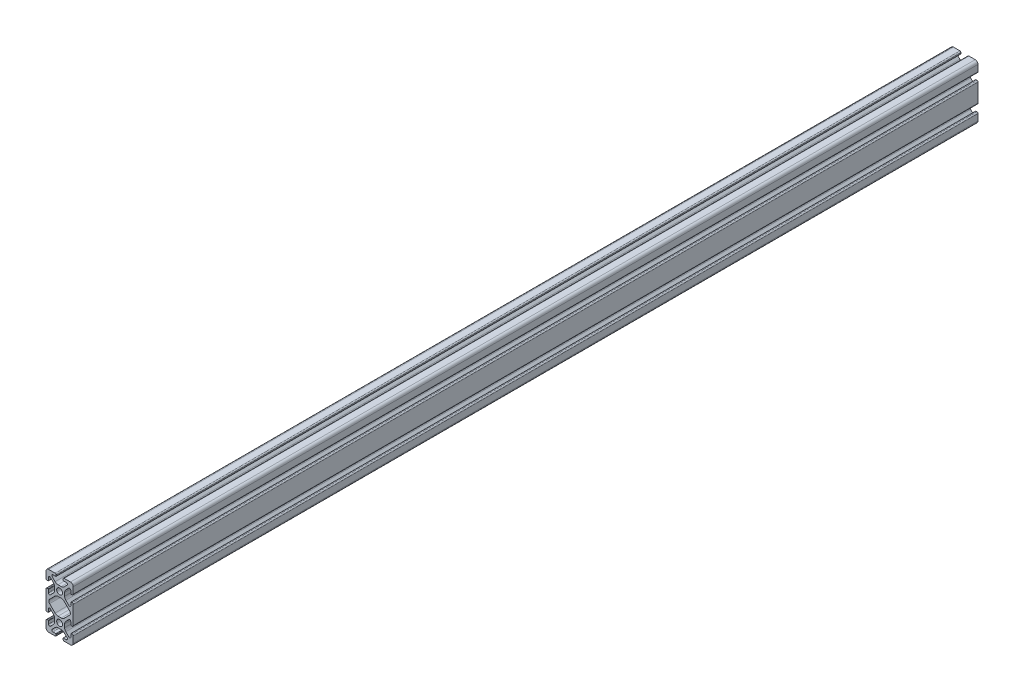
SolidWorks part; units mm, degrees
ref_plane "Front Plane" through (0, 0, 0) normal (0, 0, 1) x (1, 0, 0)
ref_plane "Top Plane" through (0, 0, 0) normal (0, 1, 0) x (1, 0, 0)
ref_plane "Right Plane" through (0, 0, 0) normal (1, 0, 0) x (0, 0, -1)
sketch "Sketch1" plane through (0, 0, 0) normal (0, 0, 1) x (1, 0, 0)
  line L0 (0, 10) -> (0, 20) construction
  line L1 (0, 10) -> (10, 10) construction
  line L2 (0, 10) -> (-10, 20) construction
  line L3 (-8, 20) -> (-3.3, 20)
  line L4 (-10, 20) -> (0, 20) construction
  line L6 (-2.8, 18.2) -> (-4.9051, 18.2)
  line L10 (0, 13.7) -> (-1.2022, 13.7)
  line L11 (-3.3236, 14.5787) -> (-5.5025, 16.7576)
  line L24 (0, 10) -> (-10, 10) construction
  line L25 (-10, 10) -> (0, 10) construction
  line L27 (-10, 0) -> (-10, 20) construction
  line L28 (0, 20) -> (10, 20) construction
  line L29 (-2.5, 18.5) -> (-2.5, 19.2)
  line L30 (-10, -20) -> (10, -20) construction
  line L31 (0, 20) -> (0, -20) construction
  arc A0 (-9.4142, 19.4142) -> (-8, 20) centre (-8, 18) cw
  arc A5 (-3.3, 20) -> (-2.5, 19.2) centre (-3.3, 19.2) cw
  arc A6 (-1.2022, 13.7) -> (-3.3236, 14.5787) centre (-1.2022, 16.7) cw
  circle A16 centre (0, 10) radius 2.15
  arc A18 (-5.5025, 16.7576) -> (-4.9051, 18.2) centre (-4.9051, 17.3551) cw
  arc A20 (-2.8, 18.2) -> (-2.5, 18.5) centre (-2.8, 18.5) ccw
  point P15 (0, -20)
  point P24 (0, 0)
  point P42 (-2.4449, 13.7)
  point P80 (-10, 10)
  dimension "D11" = 2
  dimension "D15" = 3
  dimension "Center Hole Diameter" = 4.3
  dimension "D7" = 0.8
  dimension "D8" = 0.3
  dimension "D4" = 0.8449
  dimension "D1" = 45
  dimension "Rail Width" = 20
  dimension "T-Slot Depth" = 6.3
  dimension "D9" = 1.8
  dimension "D23" = 7.4
  dimension "D5" = 11.5
  dimension "T-Slot Width" = 5
  dimension "D3" = 1.775
  dimension "D6" = 9.8102
  dimension "Rail Height" = 40
sketch "Sketch2" plane through (0, 0, 0) normal (1, 0, 0) x (0, 0, -1)
  line L0 (-304.8, 0) -> (304.8, 0)
  line L1 (-304.8, -20) -> (-304.8, 20)
  line L2 (0, 10) -> (0, 20) construction
  line L3 (0, 0) -> (0, 20) construction
  line L4 (304.8, -20) -> (304.8, 20)
  line L5 (-10, 10) -> (10, 10) construction
  point P0 (-279.8, 0)
  point P3 (0, 0)
  point P7 (279.8, 0)
  point P11 (-304.8, 0)
  point P14 (304.8, 0)
  point P23 (0, 10)
  dimension "D1" = 25
  dimension "Length" = 609.6
sketch "Sketch3" plane through (0, 0, 0) normal (0, 0, 1) x (1, 0, 0)
  line L0 (-2.5, 18.5) -> (-2.5, 19.2) construction
  line L1 (0, 10) -> (-10, 20) construction
  line L2 (0, 10) -> (-10, 20) construction
  line L5 (-8, 20) -> (-3.3, 20) construction
  line L6 (-2.8, 18.2) -> (-4.9051, 18.2) construction
  line L7 (-8.5, 7.5) -> (-9.2, 7.5)
  line L17 (-2.5, 18.5) -> (-2.5, 19.2)
  line L19 (-2.8, 18.2) -> (-4.9051, 18.2)
  line L21 (-3.7, 10) -> (0, 10) construction
  line L22 (-3.7, 8.7978) -> (-3.7, 11.2022)
  line L23 (-4.5787, 13.3236) -> (-6.7576, 15.5025)
  line L42 (-3.3236, 14.5787) -> (-5.5025, 16.7576) construction
  line L43 (0, 13.7) -> (-1.2022, 13.7) construction
  line L44 (-8, 20) -> (-3.3, 20)
  line L47 (-3.3236, 14.5787) -> (-5.5025, 16.7576)
  line L48 (1.2022, 13.7) -> (-1.2022, 13.7)
  line L59 (0, 13.7) -> (0, 12.15) construction
  line L60 (-10, 18) -> (-10, 13.3)
  line L61 (-8.2, 12.8) -> (-8.2, 14.9051)
  line L62 (-8.5, 12.5) -> (-9.2, 12.5)
  line L63 (-8.2, 7.2) -> (-8.2, 5.0949)
  line L64 (-10, 0) -> (-10, 6.7)
  line L65 (1.2022, 6.3) -> (-1.2022, 6.3)
  line L66 (-3.3236, 5.4213) -> (-7.3307, 1.4142)
  line L68 (-4.5787, 6.6764) -> (-6.7576, 4.4975)
  line L73 (10, 0) -> (-10, 0) construction
  line L78 (4.5787, 6.6764) -> (6.7576, 4.4975)
  line L79 (3.3236, 5.4213) -> (7.3307, 1.4142)
  line L81 (10, 0) -> (10, 6.7)
  line L82 (8.2, 7.2) -> (8.2, 5.0949)
  line L83 (8.5, 12.5) -> (9.2, 12.5)
  line L84 (8.2, 12.8) -> (8.2, 14.9051)
  line L85 (10, 18) -> (10, 13.3)
  line L87 (3.3236, 14.5787) -> (5.5025, 16.7576)
  line L88 (8, 20) -> (3.3, 20)
  line L89 (4.5787, 13.3236) -> (6.7576, 15.5025)
  line L90 (3.7, 8.7978) -> (3.7, 11.2022)
  line L91 (2.8, 18.2) -> (4.9051, 18.2)
  line L92 (2.5, 18.5) -> (2.5, 19.2)
  line L93 (8.5, 7.5) -> (9.2, 7.5)
  line L94 (-10, 0) -> (-7.9165, 0)
  line L96 (7.9165, 0) -> (10, 0)
  arc A0 (-8, 20) -> (-9.4142, 19.4142) centre (-8, 18) ccw construction
  arc A1 (-2.8, 18.2) -> (-2.5, 18.5) centre (-2.8, 18.5) ccw construction
  arc A3 (-2.8, 18.2) -> (-2.5, 18.5) centre (-2.8, 18.5) ccw
  arc A5 (-8, 20) -> (-10, 18) centre (-8, 18) ccw
  arc A10 (-3.3236, 5.4213) -> (-1.2022, 6.3) centre (-1.2022, 3.3) cw
  circle A13 centre (0, 10) radius 2.15 construction
  circle A14 centre (0, 10) radius 2.15
  arc A15 (-4.5787, 13.3236) -> (-3.7, 11.2022) centre (-6.7, 11.2022) cw
  arc A16 (-8.2, 14.9051) -> (-6.7576, 15.5025) centre (-7.3551, 14.9051) cw
  arc A17 (-9.2, 12.5) -> (-10, 13.3) centre (-9.2, 13.3) cw
  arc A18 (-8.2, 12.8) -> (-8.5, 12.5) centre (-8.5, 12.8) cw
  arc A36 (-2.5, 19.2) -> (-3.3, 20) centre (-3.3, 19.2) ccw construction
  arc A38 (-4.9051, 18.2) -> (-5.5025, 16.7576) centre (-4.9051, 17.3551) ccw construction
  arc A39 (-3.3236, 14.5787) -> (-1.2022, 13.7) centre (-1.2022, 16.7) ccw construction
  arc A41 (-2.5, 19.2) -> (-3.3, 20) centre (-3.3, 19.2) ccw
  arc A43 (-4.9051, 18.2) -> (-5.5025, 16.7576) centre (-4.9051, 17.3551) ccw
  arc A44 (-3.3236, 14.5787) -> (-1.2022, 13.7) centre (-1.2022, 16.7) ccw
  arc A47 (-8.2, 7.2) -> (-8.5, 7.5) centre (-8.5, 7.2) ccw
  arc A48 (-9.2, 7.5) -> (-10, 6.7) centre (-9.2, 6.7) ccw
  arc A49 (-8.2, 5.0949) -> (-6.7576, 4.4975) centre (-7.3551, 5.0949) ccw
  arc A50 (-4.5787, 6.6764) -> (-3.7, 8.7978) centre (-6.7, 8.7978) ccw
  arc A54 (-7.9165, 0) -> (-7.3307, 1.4142) centre (-5.9165, 0) cw
  arc A57 (7.9165, 0) -> (7.3307, 1.4142) centre (5.9165, 0) ccw
  arc A58 (4.5787, 6.6764) -> (3.7, 8.7978) centre (6.7, 8.7978) cw
  arc A59 (8.2, 5.0949) -> (6.7576, 4.4975) centre (7.3551, 5.0949) cw
  arc A60 (9.2, 7.5) -> (10, 6.7) centre (9.2, 6.7) cw
  arc A61 (8.2, 7.2) -> (8.5, 7.5) centre (8.5, 7.2) cw
  arc A62 (3.3236, 14.5787) -> (1.2022, 13.7) centre (1.2022, 16.7) cw
  arc A63 (4.9051, 18.2) -> (5.5025, 16.7576) centre (4.9051, 17.3551) cw
  arc A64 (2.5, 19.2) -> (3.3, 20) centre (3.3, 19.2) cw
  arc A65 (8.2, 12.8) -> (8.5, 12.5) centre (8.5, 12.8) ccw
  arc A66 (9.2, 12.5) -> (10, 13.3) centre (9.2, 13.3) ccw
  arc A67 (8.2, 14.9051) -> (6.7576, 15.5025) centre (7.3551, 14.9051) ccw
  arc A68 (4.5787, 13.3236) -> (3.7, 11.2022) centre (6.7, 11.2022) ccw
  arc A70 (3.3236, 5.4213) -> (1.2022, 6.3) centre (1.2022, 3.3) ccw
  arc A71 (8, 20) -> (10, 18) centre (8, 18) cw
  arc A72 (2.8, 18.2) -> (2.5, 18.5) centre (2.8, 18.5) cw
  point P59 (-10, 2)
  point P71 (0, 0)
  point P116 (0, 6.3)
extrude "Boss-Extrude1" add sketch "Sketch3" along normal mid plane 609.6
pattern_circular "CirPattern1" count 2 over 360 about axis through (0, 0, 0) along (0, 0, 1) of "Boss-Extrude1"
sketch "Sketch4" plane through (0, 0, 304.8) normal (0, 0, 1) x (1, 0, 0)
  line L0 (7.3307, -1.4142) -> (3.3236, -5.4213) construction
  line L1 (-3.3236, -5.4213) -> (-7.3307, -1.4142) construction
  line L2 (1.2022, -6.3) -> (-1.2022, -6.3) construction
  line L3 (3.3236, 5.4213) -> (7.3307, 1.4142) construction
  line L4 (-1.2022, 6.3) -> (1.2022, 6.3) construction
  line L5 (-7.3307, 1.4142) -> (-3.3236, 5.4213) construction
  line L6 (7.3307, -1.4142) -> (3.3236, -5.4213)
  line L7 (-3.3236, -5.4213) -> (-7.3307, -1.4142)
  line L8 (1.2022, -6.3) -> (-1.2022, -6.3)
  line L9 (3.3236, 5.4213) -> (7.3307, 1.4142)
  line L10 (-1.2022, 6.3) -> (1.2022, 6.3)
  line L11 (-7.3307, 1.4142) -> (-3.3236, 5.4213)
  line L52 (-2.5, 18.5) -> (-2.5, 19.2)
  line L53 (-3.3, 20) -> (-8, 20)
  line L54 (-10, 18) -> (-10, 13.3)
  line L55 (-9.2, 12.5) -> (-8.5, 12.5)
  line L56 (-8.2, 12.8) -> (-8.2, 14.9051)
  line L57 (-6.7576, 15.5025) -> (-4.5787, 13.3236)
  line L58 (-3.7, 11.2022) -> (-3.7, 8.7978)
  line L59 (-4.5787, 6.6764) -> (-6.7576, 4.4975)
  line L60 (-8.2, 5.0949) -> (-8.2, 7.2)
  line L61 (-8.5, 7.5) -> (-9.2, 7.5)
  line L62 (-10, 6.7) -> (-10, -6.7)
  line L63 (-9.2, -7.5) -> (-8.5, -7.5)
  line L64 (-8.2, -7.2) -> (-8.2, -5.0949)
  line L65 (-6.7576, -4.4975) -> (-4.5787, -6.6764)
  line L66 (-3.7, -8.7978) -> (-3.7, -11.2022)
  line L67 (-4.5787, -13.3236) -> (-6.7576, -15.5025)
  line L68 (-8.2, -14.9051) -> (-8.2, -12.8)
  line L69 (-8.5, -12.5) -> (-9.2, -12.5)
  line L70 (-10, -13.3) -> (-10, -18)
  line L71 (-8, -20) -> (-3.3, -20)
  line L72 (-2.5, -19.2) -> (-2.5, -18.5)
  line L73 (-2.8, -18.2) -> (-4.9051, -18.2)
  line L74 (-5.5025, -16.7576) -> (-3.3236, -14.5787)
  line L75 (-1.2022, -13.7) -> (1.2022, -13.7)
  line L76 (3.3236, -14.5787) -> (5.5025, -16.7576)
  line L77 (4.9051, -18.2) -> (2.8, -18.2)
  line L78 (2.5, -18.5) -> (2.5, -19.2)
  line L79 (3.3, -20) -> (8, -20)
  line L80 (10, -18) -> (10, -13.3)
  line L81 (9.2, -12.5) -> (8.5, -12.5)
  line L82 (8.2, -12.8) -> (8.2, -14.9051)
  line L83 (6.7576, -15.5025) -> (4.5787, -13.3236)
  line L84 (3.7, -11.2022) -> (3.7, -8.7978)
  line L85 (4.5787, -6.6764) -> (6.7576, -4.4975)
  line L86 (8.2, -5.0949) -> (8.2, -7.2)
  line L87 (8.5, -7.5) -> (9.2, -7.5)
  line L88 (10, -6.7) -> (10, 6.7)
  line L89 (9.2, 7.5) -> (8.5, 7.5)
  line L90 (8.2, 7.2) -> (8.2, 5.0949)
  line L91 (6.7576, 4.4975) -> (4.5787, 6.6764)
  line L92 (3.7, 8.7978) -> (3.7, 11.2022)
  line L93 (4.5787, 13.3236) -> (6.7576, 15.5025)
  line L94 (8.2, 14.9051) -> (8.2, 12.8)
  line L95 (8.5, 12.5) -> (9.2, 12.5)
  line L96 (10, 13.3) -> (10, 18)
  line L97 (8, 20) -> (3.3, 20)
  line L98 (2.5, 19.2) -> (2.5, 18.5)
  line L99 (2.8, 18.2) -> (4.9051, 18.2)
  line L100 (5.5025, 16.7576) -> (3.3236, 14.5787)
  line L101 (1.2022, 13.7) -> (-1.2022, 13.7)
  line L102 (-3.3236, 14.5787) -> (-5.5025, 16.7576)
  line L103 (-4.9051, 18.2) -> (-2.8, 18.2)
  line L104 (-2.5, 18.5) -> (-2.5, 19.2)
  line L105 (-3.3, 20) -> (-8, 20)
  line L106 (-10, 18) -> (-10, 13.3)
  line L107 (-9.2, 12.5) -> (-8.5, 12.5)
  line L108 (-8.2, 12.8) -> (-8.2, 14.9051)
  line L109 (-6.7576, 15.5025) -> (-4.5787, 13.3236)
  line L110 (-3.7, 11.2022) -> (-3.7, 8.7978)
  line L111 (-4.5787, 6.6764) -> (-6.7576, 4.4975)
  line L112 (-8.2, 5.0949) -> (-8.2, 7.2)
  line L113 (-8.5, 7.5) -> (-9.2, 7.5)
  line L114 (-10, 6.7) -> (-10, -6.7)
  line L115 (-9.2, -7.5) -> (-8.5, -7.5)
  line L116 (-8.2, -7.2) -> (-8.2, -5.0949)
  line L117 (-6.7576, -4.4975) -> (-4.5787, -6.6764)
  line L118 (-3.7, -8.7978) -> (-3.7, -11.2022)
  line L119 (-4.5787, -13.3236) -> (-6.7576, -15.5025)
  line L120 (-8.2, -14.9051) -> (-8.2, -12.8)
  line L121 (-8.5, -12.5) -> (-9.2, -12.5)
  line L122 (-10, -13.3) -> (-10, -18)
  line L123 (-8, -20) -> (-3.3, -20)
  line L124 (-2.5, -19.2) -> (-2.5, -18.5)
  line L125 (-2.8, -18.2) -> (-4.9051, -18.2)
  line L126 (-5.5025, -16.7576) -> (-3.3236, -14.5787)
  line L127 (-1.2022, -13.7) -> (1.2022, -13.7)
  line L128 (3.3236, -14.5787) -> (5.5025, -16.7576)
  line L129 (4.9051, -18.2) -> (2.8, -18.2)
  line L130 (2.5, -18.5) -> (2.5, -19.2)
  line L131 (3.3, -20) -> (8, -20)
  line L132 (10, -18) -> (10, -13.3)
  line L133 (9.2, -12.5) -> (8.5, -12.5)
  line L134 (8.2, -12.8) -> (8.2, -14.9051)
  line L135 (6.7576, -15.5025) -> (4.5787, -13.3236)
  line L136 (3.7, -11.2022) -> (3.7, -8.7978)
  line L137 (4.5787, -6.6764) -> (6.7576, -4.4975)
  line L138 (8.2, -5.0949) -> (8.2, -7.2)
  line L139 (8.5, -7.5) -> (9.2, -7.5)
  line L140 (10, -6.7) -> (10, 6.7)
  line L141 (9.2, 7.5) -> (8.5, 7.5)
  line L142 (8.2, 7.2) -> (8.2, 5.0949)
  line L143 (6.7576, 4.4975) -> (4.5787, 6.6764)
  line L144 (3.7, 8.7978) -> (3.7, 11.2022)
  line L145 (4.5787, 13.3236) -> (6.7576, 15.5025)
  line L146 (8.2, 14.9051) -> (8.2, 12.8)
  line L147 (8.5, 12.5) -> (9.2, 12.5)
  line L148 (10, 13.3) -> (10, 18)
  line L149 (8, 20) -> (3.3, 20)
  line L150 (2.5, 19.2) -> (2.5, 18.5)
  line L151 (2.8, 18.2) -> (4.9051, 18.2)
  line L152 (5.5025, 16.7576) -> (3.3236, 14.5787)
  line L153 (1.2022, 13.7) -> (-1.2022, 13.7)
  line L154 (-3.3236, 14.5787) -> (-5.5025, 16.7576)
  line L155 (-4.9051, 18.2) -> (-2.8, 18.2)
  circle A0 centre (0, 10) radius 2.15 construction
  arc A1 (-7.3307, 1.4142) -> (-7.3307, -1.4142) centre (-5.9165, 0) ccw construction
  arc A2 (-3.3236, -5.4213) -> (-1.2022, -6.3) centre (-1.2022, -3.3) ccw construction
  arc A3 (1.2022, -6.3) -> (3.3236, -5.4213) centre (1.2022, -3.3) ccw construction
  circle A4 centre (0, -10) radius 2.15 construction
  arc A5 (7.3307, -1.4142) -> (7.3307, 1.4142) centre (5.9165, 0) ccw construction
  arc A6 (3.3236, 5.4213) -> (1.2022, 6.3) centre (1.2022, 3.3) ccw construction
  arc A7 (-1.2022, 6.3) -> (-3.3236, 5.4213) centre (-1.2022, 3.3) ccw construction
  circle A8 centre (0, 10) radius 2.15
  arc A9 (-7.3307, 1.4142) -> (-7.3307, -1.4142) centre (-5.9165, 0) ccw
  arc A10 (-3.3236, -5.4213) -> (-1.2022, -6.3) centre (-1.2022, -3.3) ccw
  arc A11 (1.2022, -6.3) -> (3.3236, -5.4213) centre (1.2022, -3.3) ccw
  circle A12 centre (0, -10) radius 2.15
  arc A13 (7.3307, -1.4142) -> (7.3307, 1.4142) centre (5.9165, 0) ccw
  arc A14 (3.3236, 5.4213) -> (1.2022, 6.3) centre (1.2022, 3.3) ccw
  arc A15 (-1.2022, 6.3) -> (-3.3236, 5.4213) centre (-1.2022, 3.3) ccw
  arc A52 (-2.8, 18.2) -> (-2.5, 18.5) centre (-2.8, 18.5) ccw
  arc A53 (-2.5, 19.2) -> (-3.3, 20) centre (-3.3, 19.2) ccw
  arc A54 (-8, 20) -> (-10, 18) centre (-8, 18) ccw
  arc A55 (-10, 13.3) -> (-9.2, 12.5) centre (-9.2, 13.3) ccw
  arc A56 (-8.5, 12.5) -> (-8.2, 12.8) centre (-8.5, 12.8) ccw
  arc A57 (-6.7576, 15.5025) -> (-8.2, 14.9051) centre (-7.3551, 14.9051) ccw
  arc A58 (-3.7, 11.2022) -> (-4.5787, 13.3236) centre (-6.7, 11.2022) ccw
  arc A59 (-4.5787, 6.6764) -> (-3.7, 8.7978) centre (-6.7, 8.7978) ccw
  arc A60 (-8.2, 5.0949) -> (-6.7576, 4.4975) centre (-7.3551, 5.0949) ccw
  arc A61 (-8.2, 7.2) -> (-8.5, 7.5) centre (-8.5, 7.2) ccw
  arc A62 (-9.2, 7.5) -> (-10, 6.7) centre (-9.2, 6.7) ccw
  arc A63 (-10, -6.7) -> (-9.2, -7.5) centre (-9.2, -6.7) ccw
  arc A64 (-8.5, -7.5) -> (-8.2, -7.2) centre (-8.5, -7.2) ccw
  arc A65 (-6.7576, -4.4975) -> (-8.2, -5.0949) centre (-7.3551, -5.0949) ccw
  arc A66 (-3.7, -8.7978) -> (-4.5787, -6.6764) centre (-6.7, -8.7978) ccw
  arc A67 (-4.5787, -13.3236) -> (-3.7, -11.2022) centre (-6.7, -11.2022) ccw
  arc A68 (-8.2, -14.9051) -> (-6.7576, -15.5025) centre (-7.3551, -14.9051) ccw
  arc A69 (-8.2, -12.8) -> (-8.5, -12.5) centre (-8.5, -12.8) ccw
  arc A70 (-9.2, -12.5) -> (-10, -13.3) centre (-9.2, -13.3) ccw
  arc A71 (-10, -18) -> (-8, -20) centre (-8, -18) ccw
  arc A72 (-3.3, -20) -> (-2.5, -19.2) centre (-3.3, -19.2) ccw
  arc A73 (-2.5, -18.5) -> (-2.8, -18.2) centre (-2.8, -18.5) ccw
  arc A74 (-5.5025, -16.7576) -> (-4.9051, -18.2) centre (-4.9051, -17.3551) ccw
  arc A75 (-1.2022, -13.7) -> (-3.3236, -14.5787) centre (-1.2022, -16.7) ccw
  arc A76 (3.3236, -14.5787) -> (1.2022, -13.7) centre (1.2022, -16.7) ccw
  arc A77 (4.9051, -18.2) -> (5.5025, -16.7576) centre (4.9051, -17.3551) ccw
  arc A78 (2.8, -18.2) -> (2.5, -18.5) centre (2.8, -18.5) ccw
  arc A79 (2.5, -19.2) -> (3.3, -20) centre (3.3, -19.2) ccw
  arc A80 (8, -20) -> (10, -18) centre (8, -18) ccw
  arc A81 (10, -13.3) -> (9.2, -12.5) centre (9.2, -13.3) ccw
  arc A82 (8.5, -12.5) -> (8.2, -12.8) centre (8.5, -12.8) ccw
  arc A83 (6.7576, -15.5025) -> (8.2, -14.9051) centre (7.3551, -14.9051) ccw
  arc A84 (3.7, -11.2022) -> (4.5787, -13.3236) centre (6.7, -11.2022) ccw
  arc A85 (4.5787, -6.6764) -> (3.7, -8.7978) centre (6.7, -8.7978) ccw
  arc A86 (8.2, -5.0949) -> (6.7576, -4.4975) centre (7.3551, -5.0949) ccw
  arc A87 (8.2, -7.2) -> (8.5, -7.5) centre (8.5, -7.2) ccw
  arc A88 (9.2, -7.5) -> (10, -6.7) centre (9.2, -6.7) ccw
  arc A89 (10, 6.7) -> (9.2, 7.5) centre (9.2, 6.7) ccw
  arc A90 (8.5, 7.5) -> (8.2, 7.2) centre (8.5, 7.2) ccw
  arc A91 (6.7576, 4.4975) -> (8.2, 5.0949) centre (7.3551, 5.0949) ccw
  arc A92 (3.7, 8.7978) -> (4.5787, 6.6764) centre (6.7, 8.7978) ccw
  arc A93 (4.5787, 13.3236) -> (3.7, 11.2022) centre (6.7, 11.2022) ccw
  arc A94 (8.2, 14.9051) -> (6.7576, 15.5025) centre (7.3551, 14.9051) ccw
  arc A95 (8.2, 12.8) -> (8.5, 12.5) centre (8.5, 12.8) ccw
  arc A96 (9.2, 12.5) -> (10, 13.3) centre (9.2, 13.3) ccw
  arc A97 (10, 18) -> (8, 20) centre (8, 18) ccw
  arc A98 (3.3, 20) -> (2.5, 19.2) centre (3.3, 19.2) ccw
  arc A99 (2.5, 18.5) -> (2.8, 18.2) centre (2.8, 18.5) ccw
  arc A100 (5.5025, 16.7576) -> (4.9051, 18.2) centre (4.9051, 17.3551) ccw
  arc A101 (1.2022, 13.7) -> (3.3236, 14.5787) centre (1.2022, 16.7) ccw
  arc A102 (-3.3236, 14.5787) -> (-1.2022, 13.7) centre (-1.2022, 16.7) ccw
  arc A103 (-4.9051, 18.2) -> (-5.5025, 16.7576) centre (-4.9051, 17.3551) ccw
  arc A104 (-2.8, 18.2) -> (-2.5, 18.5) centre (-2.8, 18.5) ccw
  arc A105 (-2.5, 19.2) -> (-3.3, 20) centre (-3.3, 19.2) ccw
  arc A106 (-8, 20) -> (-10, 18) centre (-8, 18) ccw
  arc A107 (-10, 13.3) -> (-9.2, 12.5) centre (-9.2, 13.3) ccw
  arc A108 (-8.5, 12.5) -> (-8.2, 12.8) centre (-8.5, 12.8) ccw
  arc A109 (-6.7576, 15.5025) -> (-8.2, 14.9051) centre (-7.3551, 14.9051) ccw
  arc A110 (-3.7, 11.2022) -> (-4.5787, 13.3236) centre (-6.7, 11.2022) ccw
  arc A111 (-4.5787, 6.6764) -> (-3.7, 8.7978) centre (-6.7, 8.7978) ccw
  arc A112 (-8.2, 5.0949) -> (-6.7576, 4.4975) centre (-7.3551, 5.0949) ccw
  arc A113 (-8.2, 7.2) -> (-8.5, 7.5) centre (-8.5, 7.2) ccw
  arc A114 (-9.2, 7.5) -> (-10, 6.7) centre (-9.2, 6.7) ccw
  arc A115 (-10, -6.7) -> (-9.2, -7.5) centre (-9.2, -6.7) ccw
  arc A116 (-8.5, -7.5) -> (-8.2, -7.2) centre (-8.5, -7.2) ccw
  arc A117 (-6.7576, -4.4975) -> (-8.2, -5.0949) centre (-7.3551, -5.0949) ccw
  arc A118 (-3.7, -8.7978) -> (-4.5787, -6.6764) centre (-6.7, -8.7978) ccw
  arc A119 (-4.5787, -13.3236) -> (-3.7, -11.2022) centre (-6.7, -11.2022) ccw
  arc A120 (-8.2, -14.9051) -> (-6.7576, -15.5025) centre (-7.3551, -14.9051) ccw
  arc A121 (-8.2, -12.8) -> (-8.5, -12.5) centre (-8.5, -12.8) ccw
  arc A122 (-9.2, -12.5) -> (-10, -13.3) centre (-9.2, -13.3) ccw
  arc A123 (-10, -18) -> (-8, -20) centre (-8, -18) ccw
  arc A124 (-3.3, -20) -> (-2.5, -19.2) centre (-3.3, -19.2) ccw
  arc A125 (-2.5, -18.5) -> (-2.8, -18.2) centre (-2.8, -18.5) ccw
  arc A126 (-5.5025, -16.7576) -> (-4.9051, -18.2) centre (-4.9051, -17.3551) ccw
  arc A127 (-1.2022, -13.7) -> (-3.3236, -14.5787) centre (-1.2022, -16.7) ccw
  arc A128 (3.3236, -14.5787) -> (1.2022, -13.7) centre (1.2022, -16.7) ccw
  arc A129 (4.9051, -18.2) -> (5.5025, -16.7576) centre (4.9051, -17.3551) ccw
  arc A130 (2.8, -18.2) -> (2.5, -18.5) centre (2.8, -18.5) ccw
  arc A131 (2.5, -19.2) -> (3.3, -20) centre (3.3, -19.2) ccw
  arc A132 (8, -20) -> (10, -18) centre (8, -18) ccw
  arc A133 (10, -13.3) -> (9.2, -12.5) centre (9.2, -13.3) ccw
  arc A134 (8.5, -12.5) -> (8.2, -12.8) centre (8.5, -12.8) ccw
  arc A135 (6.7576, -15.5025) -> (8.2, -14.9051) centre (7.3551, -14.9051) ccw
  arc A136 (3.7, -11.2022) -> (4.5787, -13.3236) centre (6.7, -11.2022) ccw
  arc A137 (4.5787, -6.6764) -> (3.7, -8.7978) centre (6.7, -8.7978) ccw
  arc A138 (8.2, -5.0949) -> (6.7576, -4.4975) centre (7.3551, -5.0949) ccw
  arc A139 (8.2, -7.2) -> (8.5, -7.5) centre (8.5, -7.2) ccw
  arc A140 (9.2, -7.5) -> (10, -6.7) centre (9.2, -6.7) ccw
  arc A141 (10, 6.7) -> (9.2, 7.5) centre (9.2, 6.7) ccw
  arc A142 (8.5, 7.5) -> (8.2, 7.2) centre (8.5, 7.2) ccw
  arc A143 (6.7576, 4.4975) -> (8.2, 5.0949) centre (7.3551, 5.0949) ccw
  arc A144 (3.7, 8.7978) -> (4.5787, 6.6764) centre (6.7, 8.7978) ccw
  arc A145 (4.5787, 13.3236) -> (3.7, 11.2022) centre (6.7, 11.2022) ccw
  arc A146 (8.2, 14.9051) -> (6.7576, 15.5025) centre (7.3551, 14.9051) ccw
  arc A147 (8.2, 12.8) -> (8.5, 12.5) centre (8.5, 12.8) ccw
  arc A148 (9.2, 12.5) -> (10, 13.3) centre (9.2, 13.3) ccw
  arc A149 (10, 18) -> (8, 20) centre (8, 18) ccw
  arc A150 (3.3, 20) -> (2.5, 19.2) centre (3.3, 19.2) ccw
  arc A151 (2.5, 18.5) -> (2.8, 18.2) centre (2.8, 18.5) ccw
  arc A152 (5.5025, 16.7576) -> (4.9051, 18.2) centre (4.9051, 17.3551) ccw
  arc A153 (1.2022, 13.7) -> (3.3236, 14.5787) centre (1.2022, 16.7) ccw
  arc A154 (-3.3236, 14.5787) -> (-1.2022, 13.7) centre (-1.2022, 16.7) ccw
  arc A155 (-4.9051, 18.2) -> (-5.5025, 16.7576) centre (-4.9051, 17.3551) ccw
  dimension "D1" = 0
extrude "Boss-Extrude2" add sketch "Sketch4" along normal blind 27.5
mirror "Mirror1" about plane through (0, 0, 0) normal (0, 0, 1) of "Boss-Extrude2"
equation "\"D1@Sketch2\"=\"Rail Width@Sketch1\"*1.25"
equation "\"D1@Boss-Extrude1\" = \"Length@Sketch2\""
